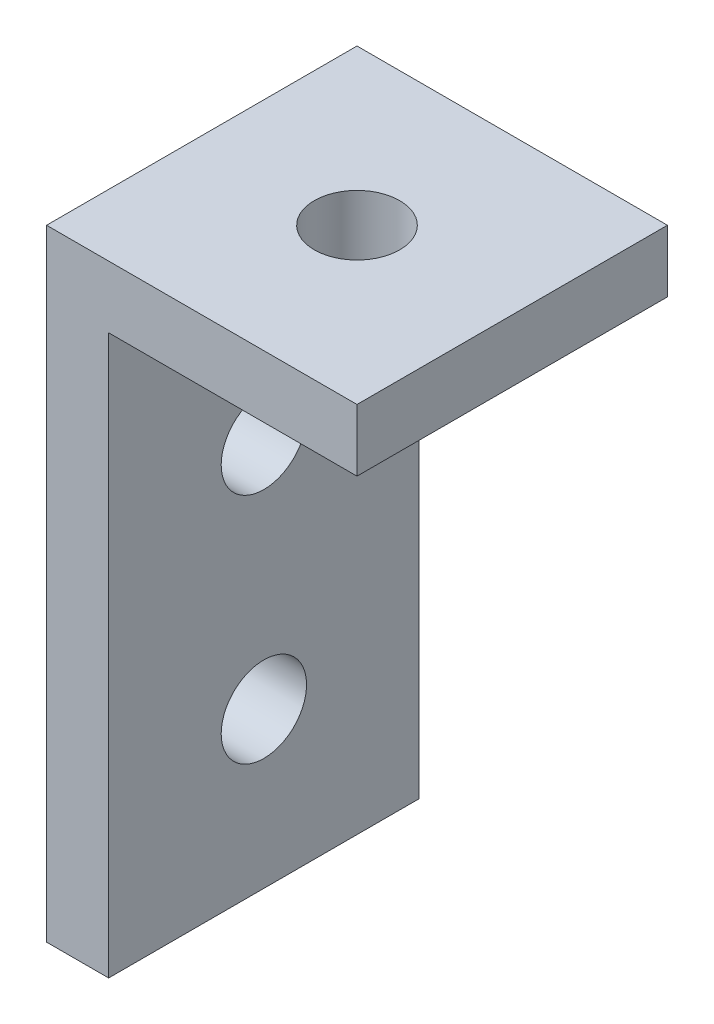
SolidWorks part; units mm, degrees
ref_plane "Front Plane" through (0, 0, 0) normal (0, 0, 1) x (1, 0, 0)
ref_plane "Top Plane" through (0, 0, 0) normal (0, 1, 0) x (1, 0, 0)
ref_plane "Right Plane" through (0, 0, 0) normal (1, 0, 0) x (0, 0, -1)
sketch "Sketch1" plane through (0, 0, 0) normal (0, 0, 1) x (1, 0, 0)
  line L0 (0, 0) -> (4, 0)
  line L1 (4, 0) -> (4, 36)
  line L2 (4, 36) -> (20, 36)
  line L3 (20, 36) -> (20, 40)
  line L4 (20, 40) -> (0, 40)
  line L5 (0, 40) -> (0, 0)
  dimension "D1" = 36
  dimension "D2" = 4
  dimension "D3" = 16
extrude "Boss-Extrude1" add sketch "Sketch1" along normal blind 20
sketch "Sketch2" plane through (0, 40, 0) normal (0, 1, 0) x (1, 0, 0)
  line L0 (20, -20) -> (20, 0) construction
  line L1 (-55, 0) -> (55, 0) construction
  circle A0 centre (10, -10) radius 2.75
  dimension "D1" = 5.5
  dimension "D2" = 10
  dimension "D3" = 10
extrude "Cut-Extrude1" cut sketch "Sketch2" against normal through all
sketch "Sketch3" plane through (0, 0, 0) normal (-1, 0, 0) x (0, 0, 1)
  line L0 (20, 0) -> (0, 0) construction
  line L1 (0, -11) -> (0, 11) construction
  circle A0 centre (10, 10) radius 2.75
  circle A1 centre (10, 25) radius 2.75
  dimension "D1" = 5.5
  dimension "D2" = 10
  dimension "D3" = 10
  dimension "D4" = 15
extrude "Cut-Extrude2" cut sketch "Sketch3" against normal through all
